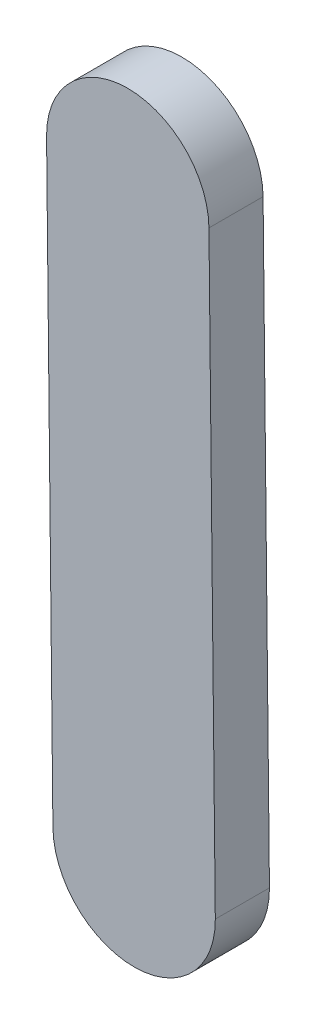
SolidWorks part; units mm, degrees
ref_plane "前视基准面" through (0, 0, 0) normal (0, 0, 1) x (1, 0, 0)
ref_plane "上视基准面" through (0, 0, 0) normal (0, 1, 0) x (1, 0, 0)
ref_plane "右视基准面" through (0, 0, 0) normal (1, 0, 0) x (0, 0, -1)
other "Configuration Table"
sketch "草图1" plane through (0, 0, 0) normal (0, 0, 1) x (1, 0, 0)
  line L0 (-48.5795, 77.5746) -> (-48.4621, 66.5752) construction
  line L1 (-47.0796, 77.5906) -> (-46.9622, 66.5913)
  line L2 (-50.0794, 77.5586) -> (-49.962, 66.5592)
  arc A0 (-47.0796, 77.5906) -> (-50.0794, 77.5586) centre (-48.5795, 77.5746) ccw
  arc A1 (-49.962, 66.5592) -> (-46.9622, 66.5913) centre (-48.4621, 66.5752) ccw
  point P2 (-48.5208, 72.0749)
extrude "凸台-拉伸2" add sketch "草图1" along normal blind 1
